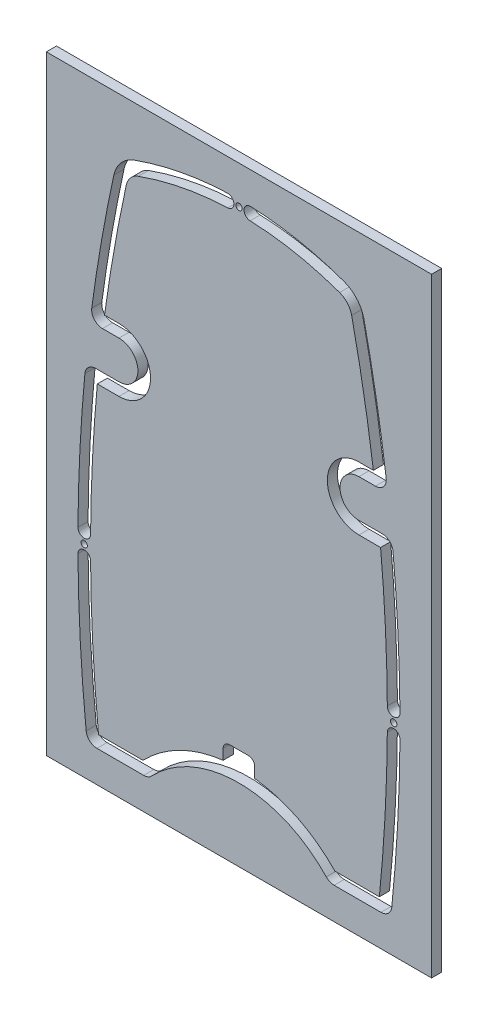
SolidWorks part; units mm, degrees
ref_plane "Ebene vorne" through (0, 0, 0) normal (0, 0, 1) x (1, 0, 0)
ref_plane "Ebene oben" through (0, 0, 0) normal (0, 1, 0) x (1, 0, 0)
ref_plane "Ebene rechts" through (0, 0, 0) normal (1, 0, 0) x (0, 0, -1)
sketch "Skizze1" plane through (0, 0, 0) normal (0, 0, 1) x (1, 0, 0)
  line L1 (-22.2316, -53) -> (-15.1905, -53)
  line L6 (-19.65, -53) -> (-19.65, -50) construction
  line L8 (-18.95, -53) -> (-18.95, -50) construction
  line L10 (-14.75, -52.5522) -> (-14.75, -50) construction
  line L12 (-14.05, -51.8924) -> (-14.05, -50) construction
  line L14 (19.8, -53) -> (19.8, -50) construction
  line L16 (18.8, -53) -> (18.8, -50) construction
  line L18 (14.75, -52.5522) -> (14.75, -50) construction
  line L20 (14.05, -51.8924) -> (14.05, -50) construction
  line L23 (15.1905, -53) -> (22.2316, -53)
  line L24 (-2.5, -46.6493) -> (-2.5, -45)
  line L25 (-1.5, -44) -> (1.5, -44)
  line L26 (2.5, -45) -> (2.5, -46.6493)
  line L27 (0, -60) -> (0, 36.5) construction
  line L28 (-19, 5) -> (-21.2856, 5)
  line L29 (-19, -5) -> (-22.4268, -5)
  line L30 (19, 5) -> (21.2856, 5)
  line L31 (19, -5) -> (22.4268, -5)
  line L32 (-22.4878, -55) -> (-15.0685, -55)
  line L36 (15.0685, -55) -> (22.4878, -55)
  line L37 (19, -3) -> (22.6852, -3)
  line L38 (19, 3) -> (21.61, 3)
  line L39 (-19, 3) -> (-21.61, 3)
  line L40 (-19, -3) -> (-22.6852, -3)
  line L41 (-0.5, -48.5066) -> (-0.5, -46) construction
  line L42 (-0.5, -46) -> (0.5, -46) construction
  line L43 (0.5, -46) -> (0.5, -48.5066) construction
  line L44 (-24.0318, -55) -> (-14.3091, -55) construction
  line L45 (14.3091, -55) -> (24.0318, -55) construction
  line L46 (19, -3) -> (24.2418, -3) construction
  line L47 (19, 3) -> (23.5627, 3) construction
  line L48 (-19, 3) -> (-23.5627, 3) construction
  line L49 (-19, -3) -> (-24.2418, -3) construction
  line L50 (-2.5, -44) -> (2.5, -44) construction
  line L51 (-30.5, 36.5) -> (30.5, 36.5)
  line L52 (-30.5, 36.5) -> (-30.5, -60)
  line L53 (-30.5, -60) -> (30.5, -60)
  line L54 (30.5, 36.5) -> (30.5, -60)
  line L55 (2.5, -44) -> (2.5, -46.6493) construction
  line L56 (-2.5, -46.6493) -> (-2.5, -44) construction
  arc A0 (22.2316, -53) -> (23.4935, -29.7927) centre (-223.5, -28) ccw
  arc A1 (15.9349, 26.7163) -> (1.7625, 29.4669) centre (0, -17.5) ccw
  arc A2 (-2.5, -46.6493) -> (-15.1905, -53) centre (0, -67.5) ccw
  arc A3 (19, 5) -> (19, -5) centre (19, 0) ccw
  arc A4 (-19, -5) -> (-19, 5) centre (-19, 0) ccw
  arc A5 (21.2856, 5) -> (17.8491, 24.532) centre (-223.5, -28) ccw
  arc A6 (-17.8491, 24.532) -> (-21.2856, 5) centre (223.5, -28) ccw
  arc A7 (-22.4268, -5) -> (-23.4935, -26.2073) centre (223.5, -28) ccw
  arc A8 (17.8491, 24.532) -> (15.9349, 26.7163) centre (14.9177, 23.894) ccw
  arc A9 (-15.9349, 26.7163) -> (-17.8491, 24.532) centre (-14.9177, 23.894) ccw
  arc A12 (15.1905, -53) -> (2.5, -46.6493) centre (0, -67.5) ccw
  arc A13 (-18.95, -50) -> (-19.65, -50) centre (-19.3, -50) ccw construction
  arc A14 (-14.05, -50) -> (-14.75, -50) centre (-14.4, -50) ccw construction
  arc A15 (14.75, -50) -> (14.05, -50) centre (14.4, -50) ccw construction
  arc A16 (19.8, -50) -> (18.8, -50) centre (19.3, -50) ccw construction
  arc A17 (-24.3938, -4.5546) -> (-25.4934, -26.1927) centre (223.5, -28) ccw
  arc A19 (13.8202, -54.4615) -> (-13.8202, -54.4615) centre (0, -67.5) ccw
  arc A20 (24.195, -53.4592) -> (25.4934, -29.8073) centre (-223.5, -28) ccw
  arc A21 (19, 3) -> (19, -3) centre (19, 0) ccw
  arc A22 (23.3111, 4.9433) -> (19.8033, 24.9574) centre (-223.5, -28) ccw
  arc A23 (19.8033, 24.9574) -> (16.6129, 28.5978) centre (14.9177, 23.894) ccw
  arc A24 (16.6129, 28.5978) -> (1.8375, 31.4655) centre (0, -17.5) ccw
  arc A25 (-16.6129, 28.5978) -> (-19.8033, 24.9574) centre (-14.9177, 23.894) ccw
  arc A26 (-19.8033, 24.9574) -> (-23.3111, 4.9433) centre (223.5, -28) ccw
  arc A27 (-19, -3) -> (-19, 3) centre (-19, 0) ccw
  arc A28 (-0.5, -48.5066) -> (-14.3091, -55) centre (0, -67.5) ccw construction
  arc A29 (14.3091, -55) -> (0.5, -48.5066) centre (0, -67.5) ccw construction
  arc A31 (-24.2418, -3) -> (-24.0318, -55) centre (223.5, -28) ccw construction
  arc A32 (-22.4878, -55) -> (-24.195, -53.4592) centre (-22.4878, -53.2838) cw
  arc A33 (-13.8202, -54.4615) -> (-15.0685, -55) centre (-15.0685, -53.2838) cw
  arc A34 (13.8202, -54.4615) -> (15.0685, -55) centre (15.0685, -53.2838) ccw
  arc A35 (24.0318, -55) -> (24.2418, -3) centre (-223.5, -28) ccw construction
  arc A36 (22.4878, -55) -> (24.195, -53.4592) centre (22.4878, -53.2838) ccw
  arc A37 (24.3938, -4.5546) -> (22.6852, -3) centre (22.6852, -4.7162) ccw
  arc A38 (23.5627, 3) -> (19.8033, 24.9574) centre (-223.5, -28) ccw construction
  arc A39 (21.61, 3) -> (23.3111, 4.9433) centre (21.61, 4.7162) ccw
  arc A40 (-19.8033, 24.9574) -> (-23.5627, 3) centre (223.5, -28) ccw construction
  arc A41 (-23.3111, 4.9433) -> (-21.61, 3) centre (-21.61, 4.7162) ccw
  arc A42 (-22.6852, -3) -> (-24.3938, -4.5546) centre (-22.6852, -4.7162) ccw
  arc A43 (1.5, -44) -> (2.5, -45) centre (1.5, -45) cw
  arc A44 (-1.5, -44) -> (-2.5, -45) centre (-1.5, -45) ccw
  circle A45 centre (0, 30.5) radius 0.5
  arc A46 (-1.7625, 29.4669) -> (-1.8375, 31.4655) centre (-1.8, 30.4662) ccw
  arc A47 (1.7625, 29.4669) -> (1.8375, 31.4655) centre (1.8, 30.4662) cw
  arc A48 (1.8, 30.4662) -> (-1.8, 30.4662) centre (0, -17.5) ccw construction
  arc A49 (-1.8375, 31.4655) -> (-16.6129, 28.5978) centre (0, -17.5) ccw
  arc A50 (16.6129, 28.5978) -> (-16.6129, 28.5978) centre (0, -17.5) ccw construction
  arc A51 (-1.7625, 29.4669) -> (-15.9349, 26.7163) centre (0, -17.5) ccw
  arc A52 (15.9349, 26.7163) -> (-15.9349, 26.7163) centre (0, -17.5) ccw construction
  circle A53 centre (-24.5, -28) radius 0.5
  circle A54 centre (24.5, -28) radius 0.5
  arc A55 (-25.4934, -26.1927) -> (-23.4935, -26.2073) centre (-24.4935, -26.2) ccw
  arc A56 (-23.4935, -29.7927) -> (-25.4934, -29.8073) centre (-24.4935, -29.8) ccw
  arc A57 (23.4935, -26.2073) -> (25.4934, -26.1927) centre (24.4935, -26.2) ccw
  arc A58 (25.4934, -29.8073) -> (23.4935, -29.7927) centre (24.4935, -29.8) ccw
  arc A59 (24.4935, -29.8) -> (24.4935, -26.2) centre (-223.5, -28) ccw construction
  arc A60 (23.4935, -26.2073) -> (22.4268, -5) centre (-223.5, -28) ccw
  arc A61 (22.2316, -53) -> (22.4268, -5) centre (-223.5, -28) ccw construction
  arc A62 (25.4934, -26.1927) -> (24.3938, -4.5546) centre (-223.5, -28) ccw
  arc A63 (-24.4935, -26.2) -> (-24.4935, -29.8) centre (223.5, -28) ccw construction
  arc A64 (-23.4935, -29.7927) -> (-22.2316, -53) centre (223.5, -28) ccw
  arc A65 (-22.4268, -5) -> (-22.2316, -53) centre (223.5, -28) ccw construction
  arc A66 (-25.4934, -29.8073) -> (-24.195, -53.4592) centre (223.5, -28) ccw
  point P140 (-24.4935, -29.8073)
  point P142 (0, 0)
  point P143 (0, 0)
  point P144 (-25.4934, -29.8)
  point P145 (-23.4935, -29.8)
  point P146 (-24.4935, -26.05)
  dimension "D3" = 247
  dimension "D4" = 21
  dimension "D19" = 10
  dimension "D21" = 19
  dimension "D22" = 19
  dimension "D23" = 19.3
  dimension "D24" = 47
  dimension "D27" = 223.5
  dimension "D25" = 3
  dimension "D12" = 14.4
  dimension "D14" = 14.4
  dimension "D29" = 2
  dimension "D30" = 30.5
  dimension "D31" = 1.7162
  dimension "D35" = 1
  dimension "D36" = 1
  dimension "D37" = 48
  dimension "D38" = 48
  dimension "D41" = 1
  dimension "D44" = 248
  dimension "D45" = 1
  dimension "D47" = 1.8
  dimension "D48" = 247
  dimension "D49" = 1.8
  dimension "D50" = 248
  dimension "D5" = 223.5
  dimension "D6" = 3
  dimension "D7" = 1
  dimension "D8" = 0.7
  dimension "D9" = 0.7
  dimension "D10" = 0.7
  dimension "D11" = 53
  dimension "D13" = 19.3
  dimension "D15" = 15.1905
  dimension "D16" = 44
  dimension "D17" = 2.5
  dimension "D18" = 5
  dimension "D20" = 53
  dimension "D26" = 25
  dimension "D28" = 35.5
  dimension "D34" = 5
  dimension "D32" = 30.5
  dimension "D33" = 36.5
  dimension "D39" = 1.8
  dimension "D40" = 1.8
  dimension "D42" = 6
  dimension "D43" = 6
  dimension "D46" = 1.8
sketch "Skizze2" plane through (0, 0, 0) normal (0, 0, 1) x (1, 0, 0)
  line L3 (-1, -5) -> (1, -5)
  line L4 (-1, -5) -> (-1, -7)
  line L5 (-1, -7) -> (1, -7)
  line L6 (1, -5) -> (1, -7)
  circle A0 centre (0, 0) radius 0.5
  point P3 (0, -5)
  point P4 (1, -6)
  dimension "D2" = 1
  dimension "D1" = 6
  dimension "D4" = 2
  dimension "D5" = 2
extrude "Aufsatz-Linear austragen1" add sketch "Skizze1" along normal blind 1.6
